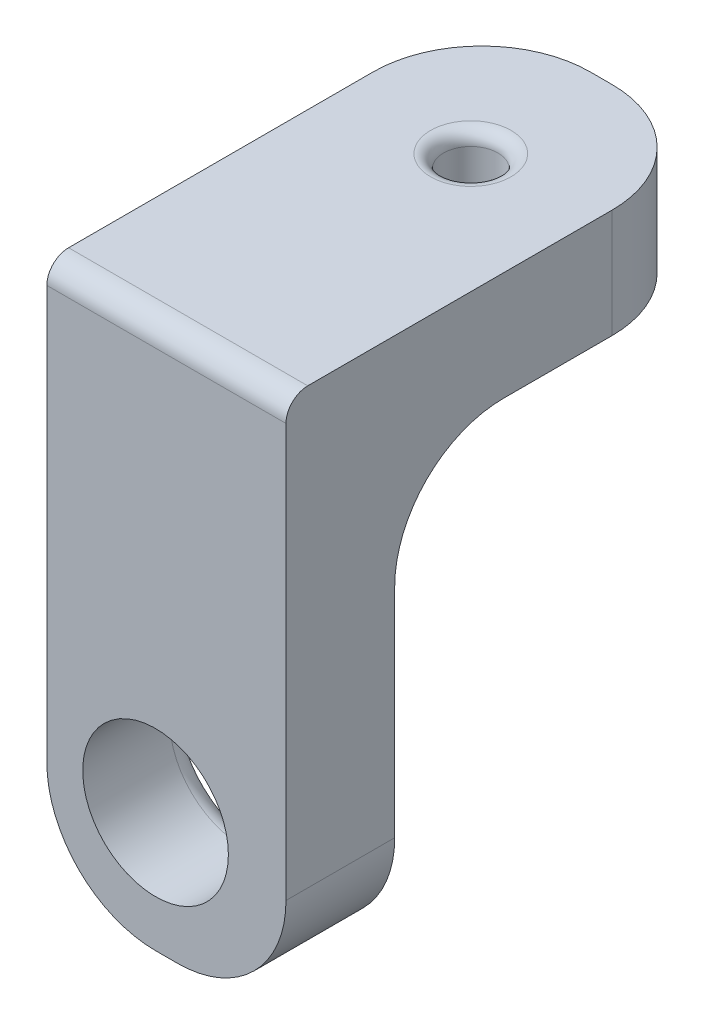
SolidWorks part; units mm, degrees
ref_plane "Спереди" through (0, 0, 0) normal (0, 0, 1) x (1, 0, 0)
ref_plane "Сверху" through (0, 0, 0) normal (0, 1, 0) x (1, 0, 0)
ref_plane "Справа" through (0, 0, 0) normal (1, 0, 0) x (0, 0, -1)
sketch "Эскиз1" plane through (0, 0, 0) normal (0, 0, 1) x (1, 0, 0)
  line L1 (-5, 14.5) -> (6, 14.5)
  line L2 (-5, 14.5) -> (-5, -5.5)
  line L3 (-5, -5.5) -> (6, -5.5)
  line L4 (6, 14.5) -> (6, -5.5)
  circle A0 centre (0, 0) radius 3.35
  dimension "D1" = 6.7
  dimension "D2" = 11
  dimension "D3" = 6
  dimension "D4" = 5.5
  dimension "D5" = 0
  dimension "D6" = 20
extrude "Бобышка-Вытянуть1" add sketch "Эскиз1" along normal blind 5
sketch "Эскиз2" plane through (0, 14.5, 0) normal (0, 1, 0) x (1, 0, 0)
  line L1 (-5, -5) -> (6, -5)
  line L2 (-5, -5) -> (-5, 15)
  line L3 (-5, 15) -> (6, 15)
  line L4 (6, -5) -> (6, 15)
  dimension "D1" = 11
  dimension "D2" = 20
extrude "Бобышка-Вытянуть2" add sketch "Эскиз2" along normal blind 5
fillet "Скругление1" radius 5 1 edges at (0.5, 14.5, 0)
fillet "Скругление2" radius 1 1 edges at (3.35, 0, 0)
fillet "Скругление4" radius 1 1 edges at (0.5, 19.5, 5)
fillet "Скругление8" radius 5 2 edges at (6, -5.5, 2.5) (-5, -5.5, 2.5)
fillet "Скругление9" radius 5 2 edges at (-5, 17, -15) (6, 17, -15)
sketch "Эскиз8" plane through (0, 14.5, 0) normal (0, -1, 0) x (1, 0, 0)
  line L0 (1, -15) -> (0, -15) construction
  line L1 (2.8094, -9) -> (1.6547, -7)
  line L2 (1.6547, -7) -> (-0.6547, -7)
  line L3 (-0.6547, -7) -> (-1.8094, -9)
  line L4 (-1.8094, -9) -> (-0.6547, -11)
  line L5 (-0.6547, -11) -> (1.6547, -11)
  line L6 (1.6547, -11) -> (2.8094, -9)
  line L8 (-5, -10) -> (-5, -5) construction
  circle A0 centre (0.5, -9) radius 2 construction
  dimension "D1" = 4
  dimension "D2" = 6
  dimension "D3" = 5.5
extrude "Вырез-Вытянуть3" cut sketch "Эскиз8" against normal blind 2
sketch "Эскиз9" plane through (0, 16.5, 0) normal (0, -1, 0) x (1, 0, 0)
  line L0 (1, -15) -> (0, -15) construction
  line L1 (-5, -10) -> (-5, -5) construction
  circle A0 centre (0.5, -9) radius 1.25
  point P6 (1.8064, -9.429)
  point P7 (0, 0)
  dimension "D1" = 2.5
  dimension "D2" = 6
  dimension "D3" = 5.5
extrude "Вырез-Вытянуть4" cut sketch "Эскиз9" against normal blind 3
fillet "Скругление10" radius 0.6 1 edges at (0.5, 19.5, -10.25)
